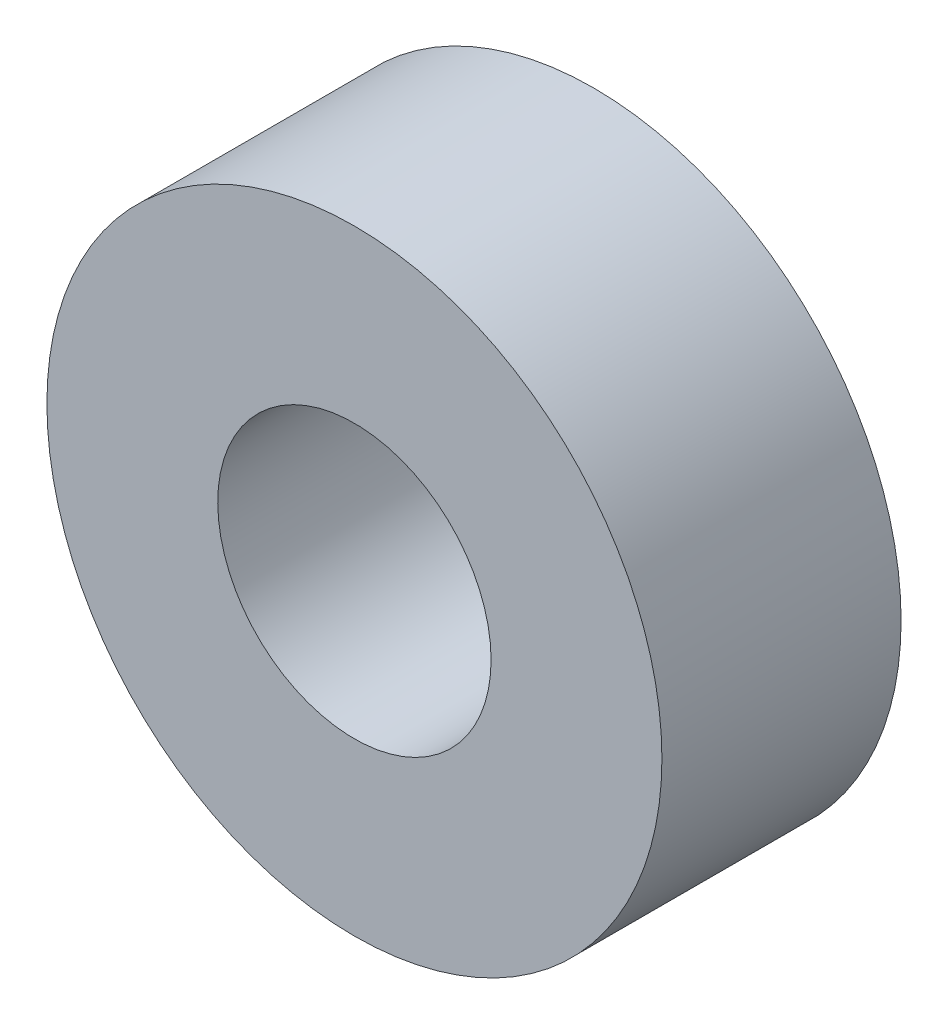
SolidWorks part; units mm, degrees
ref_plane "Front Plane" through (0, 0, 0) normal (0, 0, 1) x (1, 0, 0)
ref_plane "Top Plane" through (0, 0, 0) normal (0, 1, 0) x (1, 0, 0)
ref_plane "Right Plane" through (0, 0, 0) normal (1, 0, 0) x (0, 0, -1)
sketch "Sketch1" plane through (0, 0, 0) normal (0, 0, 1) x (1, 0, 0)
  circle A0 centre (0, 0) radius 4
  circle A1 centre (0, 0) radius 4 construction
  circle A2 centre (0, 0) radius 9
  circle A3 centre (0, 0) radius 9 construction
extrude "Boss-Extrude1" add sketch "Sketch1" along normal up to surface (7 mm away)
